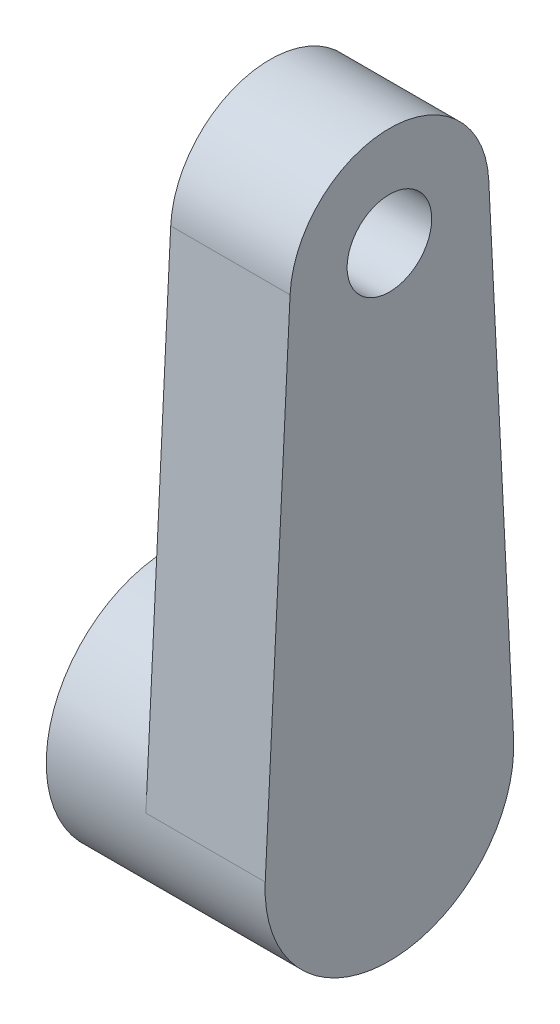
SolidWorks part; units mm, degrees
material "ABS"
ref_plane "Alzado" through (0, 0, 0) normal (0, 0, 1) x (1, 0, 0)
ref_plane "Planta" through (0, 0, 0) normal (0, 1, 0) x (1, 0, 0)
ref_plane "Vista lateral" through (0, 0, 0) normal (1, 0, 0) x (0, 0, -1)
sketch "Croquis1" plane through (0, 0, 0) normal (1, 0, 0) x (0, 0, -1)
  line L0 (-1.6583, -2.5) -> (1.6583, -2.5)
  circle A0 centre (0, 0) radius 12.5
  arc A1 (1.6583, -2.5) -> (-1.6583, -2.5) centre (0, 0) ccw
  dimension "D1" = 6
  dimension "D2" = 25
  dimension "D3" = 2.5
extrude "Saliente-Extruir1" add sketch "Croquis1" along normal blind 10
sketch "Croquis2" plane through (10, 0, 0) normal (1, 0, 0) x (0, 0, -1)
  line L0 (0, 0) -> (0, 50) construction
  line L1 (-9.9875, 50.5) -> (-12.4844, 0.625)
  line L2 (9.9875, 50.5) -> (12.4844, 0.625)
  arc A0 (9.9875, 50.5) -> (-9.9875, 50.5) centre (0, 50) ccw
  circle A1 centre (0, 0) radius 12.5 construction
  circle A3 centre (0, 0) radius 12.5
  arc A4 (-12.4844, 0.625) -> (12.4844, 0.625) centre (0, 0) ccw
  dimension "D3" = 10
  dimension "D2" = 50
  dimension "D1" = 0
extrude "Saliente-Extruir2" add sketch "Croquis2" along normal blind 12
sketch "Croquis3" plane through (0, 0, 0) normal (0, 1, 0) x (1, 0, 0)
  line L0 (0, 0) -> (10, 0) construction
  line L1 (0, 12.5) -> (0, -12.5) construction
  line L2 (10, 9.9875) -> (10, -9.9875) construction
  circle A0 centre (5, 0) radius 2.25
  dimension "D1" = 4.5
extrude "Cortar-Extruir1" cut sketch "Croquis3" against normal through all
sketch "Croquis4" plane through (22, 0, 0) normal (1, 0, 0) x (0, 0, -1)
  circle A0 centre (0, 50) radius 4.25
  dimension "D1" = 8.5
extrude "Cortar-Extruir2" cut sketch "Croquis4" against normal through all
